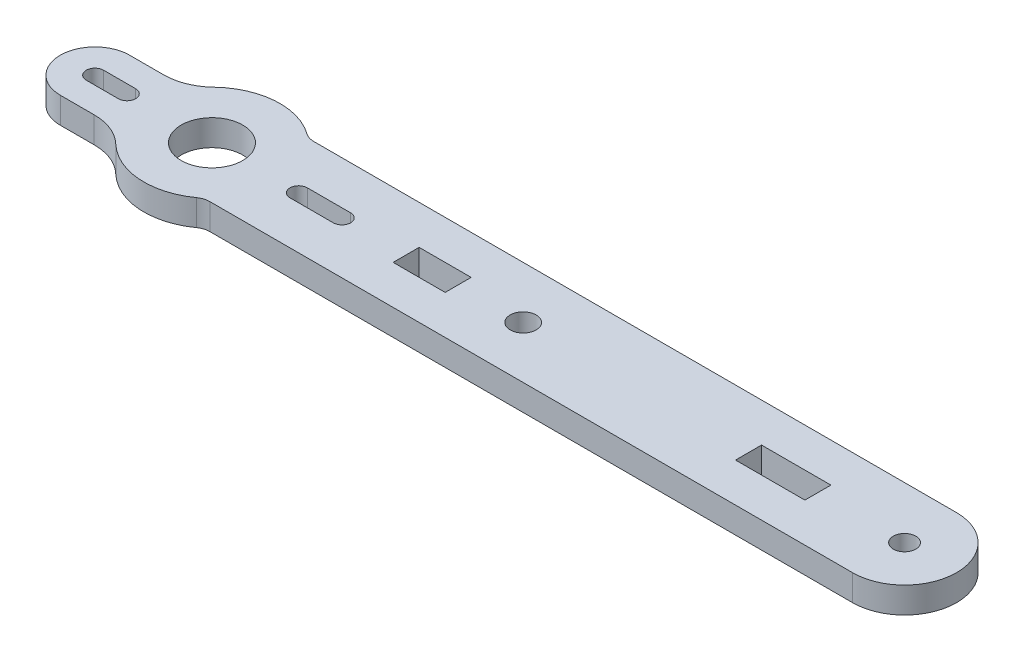
SolidWorks part; units mm, degrees
material "Acrílico (médio-alto impacto)"
ref_plane "Plano frontal" through (0, 0, 0) normal (0, 0, 1) x (1, 0, 0)
ref_plane "Plano superior" through (0, 0, 0) normal (0, 1, 0) x (1, 0, 0)
ref_plane "Plano direito" through (0, 0, 0) normal (1, 0, 0) x (0, 0, -1)
sketch "Esboço1" plane through (0, 0, 0) normal (0, 1, 0) x (1, 0, 0)
  line L0 (0, 0) -> (93.4, 0) construction
  line L1 (93.4, 6) -> (18.5619, 6)
  line L2 (93.4, -6) -> (18.5619, -6)
  line L3 (0, 4) -> (6.7456, 4)
  line L4 (0, -4) -> (6.7456, -4)
  line L5 (93.4, 0) -> (49.4, 0) construction
  circle A0 centre (0, 0) radius 4
  circle A1 centre (93.4, 0) radius 6
  circle A2 centre (13.5, 0) radius 7.85
  dimension "D2" = 15.7
  dimension "D3" = 8
  dimension "D4" = 12
  dimension "D1" = 93.4
  dimension "D5" = 13.5
  dimension "D6" = 44
sketch "Esboço2" plane through (0, 0, 0) normal (0, 1, 0) x (1, 0, 0)
  line L0 (0, 0) -> (3.7, 0) construction
  line L1 (0, 0) -> (93.4, 0) construction
  line L2 (0, 1) -> (3.7, 1)
  line L3 (0, -1) -> (3.7, -1)
  line L4 (23.5, 0) -> (28.5, 0) construction
  line L5 (23.5, 1) -> (28.5, 1)
  line L6 (23.5, -1) -> (28.5, -1)
  arc A0 (0, 1) -> (0, -1) centre (0, 0) ccw
  arc A1 (3.7, -1) -> (3.7, 1) centre (3.7, 0) ccw
  arc A2 (23.5, 1) -> (23.5, -1) centre (23.5, 0) ccw
  arc A3 (28.5, -1) -> (28.5, 1) centre (28.5, 0) ccw
  point P5 (1.85, 0)
  point P10 (26, 0)
  dimension "D1" = 3.7
  dimension "D2" = 5
  dimension "D3" = 10
  dimension "D4" = 2
sketch "Esboço3" plane through (0, 0, 0) normal (0, 1, 0) x (1, 0, 0)
  line L0 (0, 0) -> (93.4, 0) construction
  line L1 (75.4, -1.5) -> (83.4, -1.5)
  line L2 (75.4, -1.5) -> (75.4, 1.5)
  line L3 (75.4, 1.5) -> (83.4, 1.5)
  line L4 (83.4, -1.5) -> (83.4, 1.5)
  line L5 (79.4, 1.5) -> (79.4, -1.5) construction
  line L6 (75.4, 0) -> (83.4, 0) construction
  line L8 (35.9, -1.5) -> (41.9, -1.5)
  line L9 (35.9, -1.5) -> (35.9, 1.5)
  line L10 (35.9, 1.5) -> (41.9, 1.5)
  line L11 (41.9, -1.5) -> (41.9, 1.5)
  line L12 (38.9, 1.5) -> (38.9, -1.5) construction
  line L13 (35.9, 0) -> (41.9, 0) construction
  point P0 (79.4, 0)
  point P6 (38.9, 0)
  dimension "D1" = 3
  dimension "D2" = 8
  dimension "D3" = 10
  dimension "D4" = 6
  dimension "D5" = 33.5
extrude "Ressalto-extrusão1" add sketch "Esboço1" against normal blind 3 contours A0 | A2 L3 A0 L4 | A2 | A2 L2 A1 L1 | A1
hole_wizard "Furo de diâmetro Ø7.1 (7.1)1" positions "Esboço4" profile "Esboço5" hole size "Ø7.1" standard "ISO" end condition through all
sketch "Esboço4" plane through (0, 0, 0) normal (0, 1, 0) x (1, 0, 0)
  point P0 (13.5, 0)
sketch "Esboço5" plane through (13.5, 0, 0) normal (1, 0, 0) x (0, 0, 1)
  line L0 (0, 0) -> (0, 3)
  line L1 (0, 3) -> (3.55, 3)
  line L2 (3.55, 3) -> (3.55, 0)
  line L5 (3.55, 0) -> (0, 0)
  line L11 (0, -6.35) -> (0, 107.95) construction
  dimension "Thru Hole Dia." = 7.1
  dimension "Thru Hole Depth" = 3
extrude "Corte-extrusão1" cut sketch "Esboço2" against normal through all
extrude "Corte-extrusão2" cut sketch "Esboço3" against normal through all
hole_wizard "Furo de diâmetro Ø2.6 (2.6)1" positions "Esboço6" profile "Esboço7" hole size "Ø2.6" standard "ISO" end condition through all
sketch "Esboço6" plane through (0, 0, 0) normal (0, 1, 0) x (1, 0, 0)
  point P3 (93.4, 0)
sketch "Esboço7" plane through (93.4, 0, 0) normal (1, 0, 0) x (0, 0, 1)
  line L0 (0, 0) -> (0, 3)
  line L1 (0, 3) -> (1.3, 3)
  line L2 (1.3, 3) -> (1.3, 0)
  line L5 (1.3, 0) -> (0, 0)
  line L11 (0, -6.35) -> (0, 107.95) construction
  dimension "Thru Hole Dia." = 2.6
  dimension "Thru Hole Depth" = 3
hole_wizard "Furo de diâmetro Ø3.0 (3)1" positions "Esboço8" profile "Esboço9" hole size "Ø3.0" standard "ISO" end condition through all
sketch "Esboço8" plane through (0, 0, 0) normal (0, 1, 0) x (1, 0, 0)
  point P0 (49.4, 0)
sketch "Esboço9" plane through (49.4, 0, 0) normal (1, 0, 0) x (0, 0, 1)
  line L0 (0, 0) -> (0, 3)
  line L1 (0, 3) -> (1.5, 3)
  line L2 (1.5, 3) -> (1.5, 0)
  line L5 (1.5, 0) -> (0, 0)
  line L11 (0, -6.35) -> (0, 107.95) construction
  dimension "Thru Hole Dia." = 3
  dimension "Thru Hole Depth" = 3
fillet "Filete1" radius 2 2 edges at (18.5619, -1.5, 6) (18.5619, -1.5, -6)
fillet "Filete2" radius 6 2 edges at (6.7456, -1.5, 4) (6.7456, -1.5, -4)
